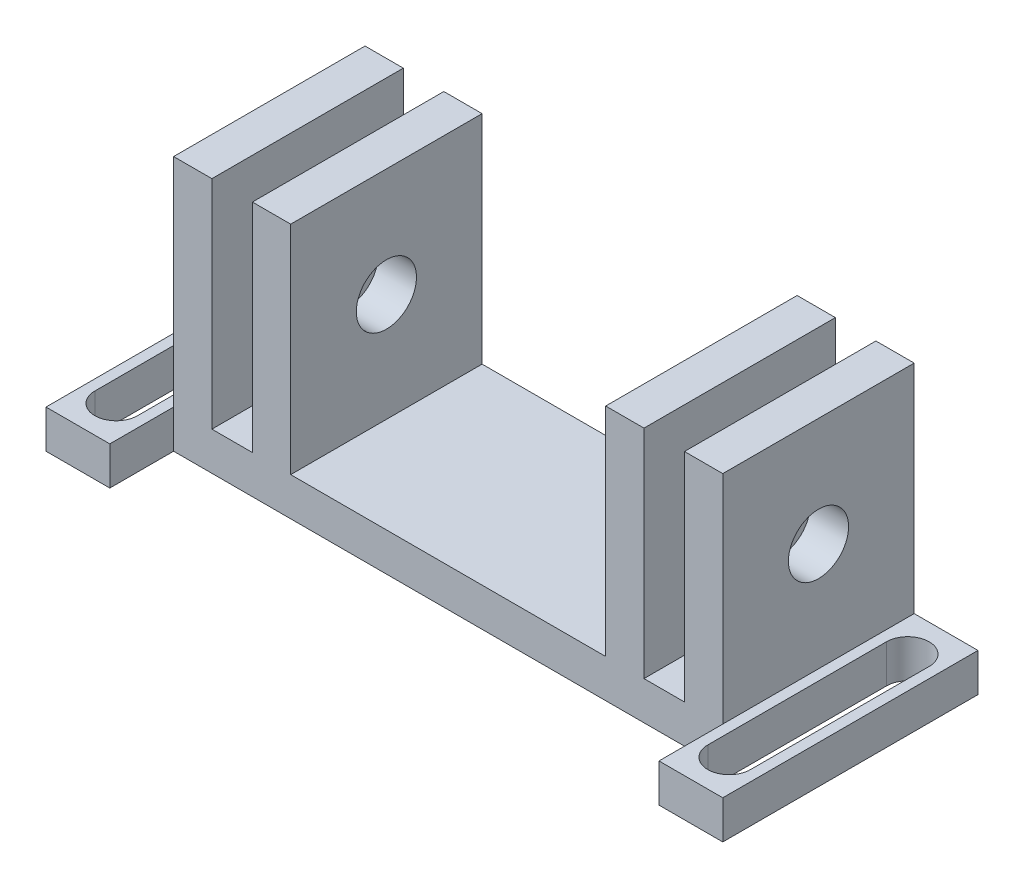
SolidWorks part; units mm, degrees
ref_plane "Front Plane" through (0, 0, 0) normal (0, 0, 1) x (1, 0, 0)
ref_plane "Top Plane" through (0, 0, 0) normal (0, 1, 0) x (1, 0, 0)
ref_plane "Right Plane" through (0, 0, 0) normal (1, 0, 0) x (0, 0, -1)
sketch "Sketch1" plane through (0, 0, 0) normal (0, 1, 0) x (1, 0, 0)
  line L1 (-15.3423, -7.5) -> (15.3423, -7.5)
  line L2 (-15.3423, -7.5) -> (-15.3423, 7.5)
  line L3 (-15.3423, 7.5) -> (15.3423, 7.5)
  line L4 (15.3423, -7.5) -> (15.3423, 7.5)
  line L5 (-15.3423, -7.5) -> (15.3423, 7.5) construction
  line L6 (-15.3423, 7.5) -> (15.3423, -7.5) construction
  point P0 (0, 0)
  dimension "D1" = 30.6846
  dimension "D2" = 15
extrude "Boss-Extrude1" add sketch "Sketch1" along normal blind 3
sketch "Sketch2" plane through (0, 3, 0) normal (0, 1, 0) x (1, 0, 0)
  line L0 (-15.3423, -7.5) -> (15.3423, -7.5) construction
  line L1 (-15.3423, 7.5) -> (-12.3423, 7.5)
  line L2 (-15.3423, 7.5) -> (-15.3423, -7.5)
  line L3 (-15.3423, -7.5) -> (-12.3423, -7.5)
  line L4 (-12.3423, 7.5) -> (-12.3423, -7.5)
  line L6 (15.3423, 7.5) -> (12.3423, 7.5)
  line L7 (15.3423, 7.5) -> (15.3423, -7.5)
  line L8 (15.3423, -7.5) -> (12.3423, -7.5)
  line L9 (12.3423, 7.5) -> (12.3423, -7.5)
  dimension "D1" = 3
  dimension "D2" = 3
extrude "Boss-Extrude2" add sketch "Sketch2" along normal blind 17
sketch "Sketch4" plane through (0, 0, 7.5) normal (0, 0, 1) x (1, 0, 0)
  line L1 (-12.3423, 3) -> (-18.5173, 3)
  line L2 (-12.3423, 3) -> (-12.3423, 0)
  line L3 (-12.3423, 0) -> (-18.5173, 0)
  line L4 (-18.5173, 3) -> (-18.5173, 0)
  line L5 (12.3423, 3) -> (18.5173, 3)
  line L6 (12.3423, 3) -> (12.3423, 0)
  line L7 (12.3423, 0) -> (18.5173, 0)
  line L8 (18.5173, 3) -> (18.5173, 0)
  line L9 (-18.5173, 0) -> (-21.5173, 0)
  line L10 (-18.5173, 0) -> (-18.5173, 20)
  line L11 (-18.5173, 20) -> (-21.5173, 20)
  line L12 (-21.5173, 0) -> (-21.5173, 20)
  line L13 (18.5173, 0) -> (21.5173, 0)
  line L14 (18.5173, 0) -> (18.5173, 20)
  line L15 (18.5173, 20) -> (21.5173, 20)
  line L16 (21.5173, 0) -> (21.5173, 20)
  line M14 (15.3423, 0) -> (15.3423, 20)
  line M20 (-15.3423, 20) -> (-15.3423, 0)
  dimension "D1" = 6.175
  dimension "D2" = 6.175
  dimension "D3" = 3
  dimension "D4" = 3
  dimension "D5" = 20
  dimension "D6" = 20
extrude "Boss-Extrude3" add sketch "Sketch4" against normal up to surface (15 mm away) contours L12 L9 L4 L10 L11 | L1 L4 L3 M20 | L8 L5 L7 M14 | L13 L16 L15 L14 L8 up to face at (0, 10.75, -7.5)
sketch "Sketch3" plane through (-15.3423, 0, 0) normal (-1, 0, 0) x (0, 0, 1)
  circle A0 centre (0, 11.4772) radius 2.3582
extrude "Cut-Extrude1" cut sketch "Sketch3" against normal through all both and the other way through all
sketch "Sketch5" plane through (0, 0, 0) normal (0, -1, 0) x (-1, 0, 0)
  line L0 (-21.5173, 7.5) -> (-21.5173, -7.5) construction
  line L1 (21.5173, 7.5) -> (26.5173, 7.5)
  line L2 (21.5173, 7.5) -> (21.5173, -12.5)
  line L3 (21.5173, -12.5) -> (26.5173, -12.5)
  line L4 (26.5173, 7.5) -> (26.5173, -12.5)
  line L5 (-21.5173, 7.5) -> (-26.5173, 7.5)
  line L6 (-21.5173, 7.5) -> (-21.5173, -12.5)
  line L7 (-21.5173, -12.5) -> (-26.5173, -12.5)
  line L8 (-26.5173, 7.5) -> (-26.5173, -12.5)
  line L9 (21.5173, 7.5) -> (-21.5173, 7.5) construction
  line L11 (24.0173, 4.5) -> (24.0173, -9.5) construction
  line L12 (25.6923, 4.5) -> (25.6923, -9.5)
  line L13 (22.3423, 4.5) -> (22.3423, -9.5)
  line L15 (-24.0173, 4.5) -> (-24.0173, -9.5) construction
  line L16 (-22.3423, 4.5) -> (-22.3423, -9.5)
  line L17 (-25.6923, 4.5) -> (-25.6923, -9.5)
  arc A0 (25.6923, 4.5) -> (22.3423, 4.5) centre (24.0173, 4.5) ccw
  arc A1 (22.3423, -9.5) -> (25.6923, -9.5) centre (24.0173, -9.5) ccw
  arc A2 (-22.3423, 4.5) -> (-25.6923, 4.5) centre (-24.0173, 4.5) ccw
  arc A3 (-25.6923, -9.5) -> (-22.3423, -9.5) centre (-24.0173, -9.5) ccw
  point P15 (24.0173, -2.5)
  point P22 (-24.0173, -2.5)
  dimension "D6" = 1.675
  dimension "D8" = 1.675
  dimension "D1" = 20
  dimension "D2" = 20
  dimension "D3" = 5
  dimension "D4" = 5
  dimension "D5" = 14
  dimension "D7" = 14
extrude "Boss-Extrude4" add sketch "Sketch5" against normal blind 3
